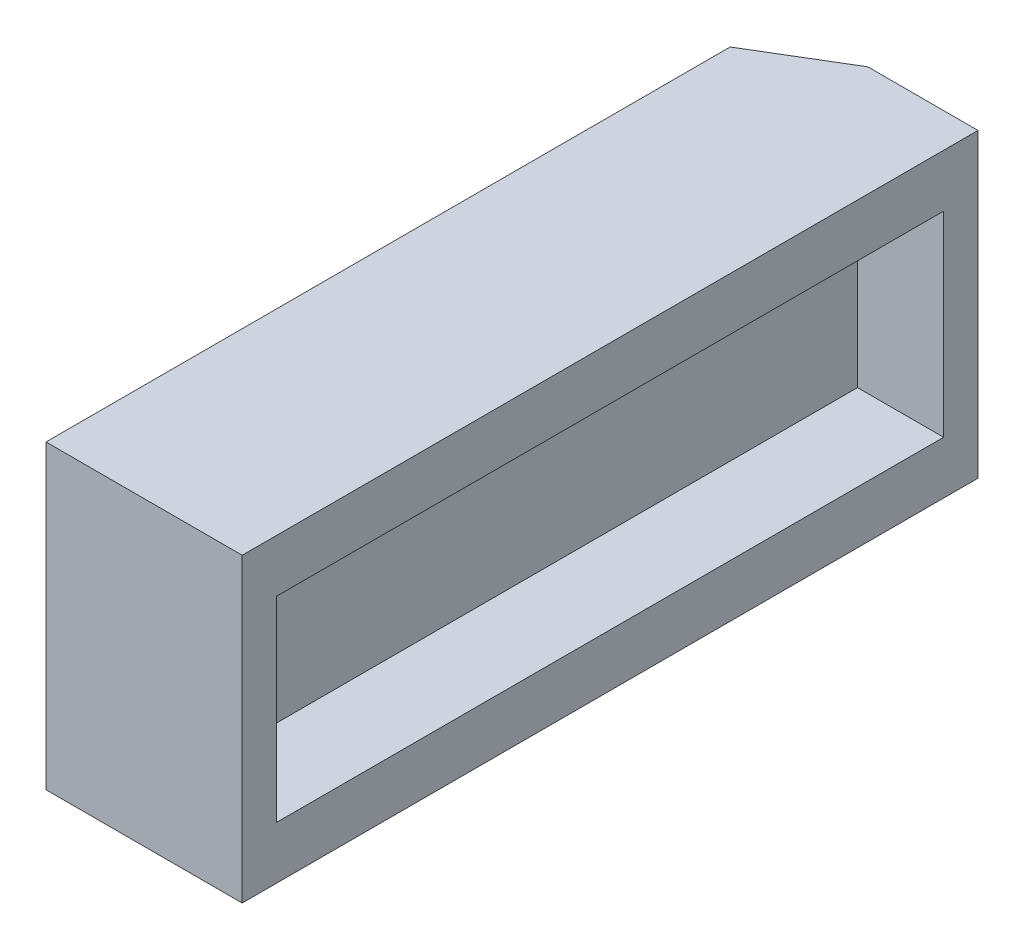
SolidWorks part; units mm, degrees
ref_plane "Front Plane" through (0, 0, 0) normal (0, 0, 1) x (1, 0, 0)
ref_plane "Top Plane" through (0, 0, 0) normal (0, 1, 0) x (1, 0, 0)
ref_plane "Right Plane" through (0, 0, 0) normal (1, 0, 0) x (0, 0, -1)
sketch "Sketch4" plane through (0, 0, 0) normal (1, 0, 0) x (0, 0, -1)
  line L0 (0, 28.9052) -> (-5.08, 28.9052) construction
  line L1 (0, 0) -> (98.425, 0)
  line L2 (0, 0) -> (0, 28.9052)
  line L3 (0, 28.9052) -> (98.425, 28.9052)
  line L4 (98.425, 0) -> (98.425, 28.9052)
  line L5 (-5.08, 36.6776) -> (103.505, 36.6776)
  line L6 (-5.08, 36.6776) -> (-5.08, -7.7724)
  line L7 (-5.08, -7.7724) -> (103.505, -7.7724)
  line L8 (103.505, 36.6776) -> (103.505, -7.7724)
  point P9 (0, 14.4526)
  point P10 (-5.08, 14.4526)
  point P11 (49.2125, 36.6776)
  point P14 (49.2125, 28.9052)
  dimension "D1" = 98.425
  dimension "D2" = 28.9052
  dimension "D3" = 44.45
  dimension "D4" = 5.08
extrude "Boss-Extrude2" add sketch "Sketch4" along normal blind 12.7
sketch "Sketch5" plane through (0, 0, 0) normal (-1, 0, 0) x (0, 0, 1)
  line L1 (-103.505, 36.6776) -> (5.08, 36.6776)
  line L2 (-103.505, 36.6776) -> (-103.505, -7.7724)
  line L3 (-103.505, -7.7724) -> (5.08, -7.7724)
  line L4 (5.08, 36.6776) -> (5.08, -7.7724)
extrude "Boss-Extrude3" add sketch "Sketch5" along normal blind 3.556
sketch "Sketch6" plane through (-3.556, 0, 0) normal (-1, 0, 0) x (0, 0, 1)
  line L0 (5.08, -7.7724) -> (5.08, 36.6776) construction
  line L1 (0, 28.9814) -> (-90.805, 28.9814)
  line L2 (0, 28.9814) -> (0, -0.0762)
  line L3 (0, -0.0762) -> (-90.805, -0.0762)
  line L4 (-90.805, 28.9814) -> (-90.805, -0.0762)
  line L6 (0, 28.9052) -> (0, 0) construction
  line L7 (-103.505, -7.7724) -> (5.08, -7.7724) construction
  line L8 (5.08, 36.6776) -> (-95.885, 36.6776)
  line L9 (5.08, 36.6776) -> (5.08, -7.7724)
  line L10 (5.08, -7.7724) -> (-95.885, -7.7724)
  line L11 (-95.885, 36.6776) -> (-95.885, -7.7724)
  point P4 (0, 14.4526)
  point P7 (5.08, 14.4526)
  point P20 (-45.4025, 28.9814)
  point P21 (-45.4025, 36.6776)
  dimension "D1" = 29.0576
  dimension "D2" = 90.805
extrude "Boss-Extrude4" add sketch "Sketch6" along normal blind 12.7
sketch "Sketch7" plane through (0, 36.6776, 0) normal (0, 1, 0) x (1, 0, 0)
  line L0 (-3.556, 103.505) -> (-3.556, 95.885)
  line L1 (-3.556, 95.885) -> (-16.256, 95.885)
  line L2 (-16.256, 95.885) -> (-3.556, 103.505)
extrude "Boss-Extrude6" add sketch "Sketch7" against normal up to surface (7.6962 mm away) up to face at (-9.906, 28.9814, -45.4025)
sketch "Sketch8" plane through (0, -7.7724, 0) normal (0, -1, 0) x (1, 0, 0)
  line L0 (-3.556, -103.505) -> (-3.556, -95.885)
  line L1 (-3.556, -95.885) -> (-16.256, -95.885)
  line L2 (-16.256, -95.885) -> (-3.556, -103.505)
extrude "Boss-Extrude7" add sketch "Sketch8" against normal up to surface (7.6962 mm away) up to face at (-9.906, -0.0762, -45.4025)
fillet "Fillet1" radius 2.54 5 edges at (-9.906, -0.0762, -95.885) (-3.556, -0.0762, -99.695) (-3.556, 14.4526, -95.885) (-9.906, 28.9814, -95.885) (-3.556, 28.9814, -99.695)
